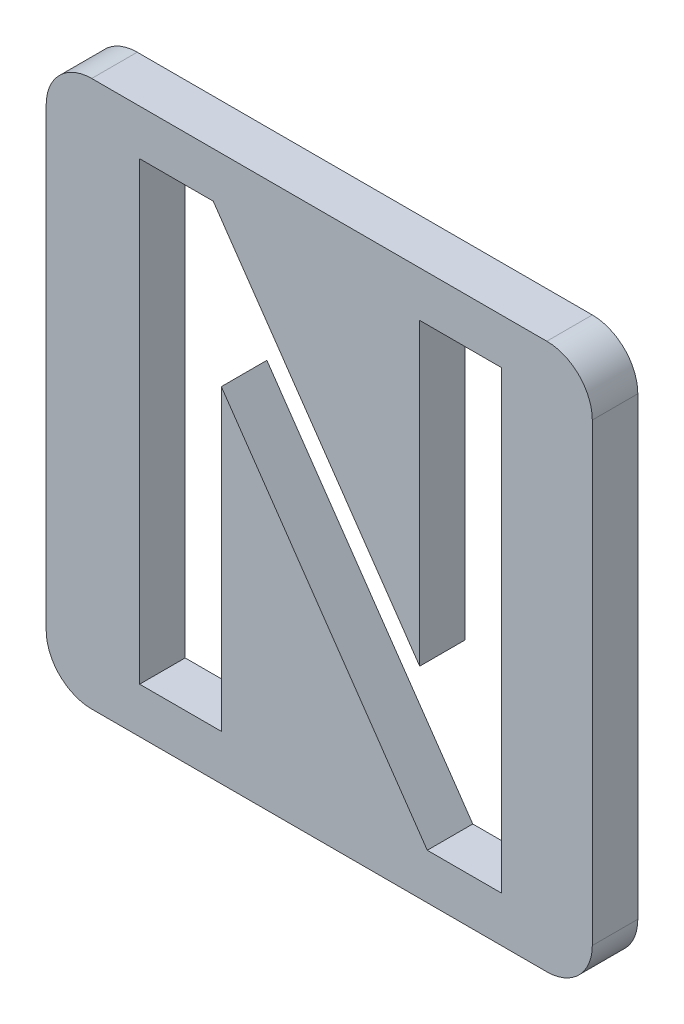
SolidWorks part; units mm, degrees
ref_plane "Front Plane" through (0, 0, 0) normal (0, 0, 1) x (1, 0, 0)
ref_plane "Top Plane" through (0, 0, 0) normal (0, 1, 0) x (1, 0, 0)
ref_plane "Right Plane" through (0, 0, 0) normal (1, 0, 0) x (0, 0, -1)
sketch "Sketch1" plane through (0, 0, 0) normal (0, 0, 1) x (1, 0, 0)
  line L1 (-50, 60) -> (50, 60)
  line L2 (-60, 50) -> (-60, -50)
  line L3 (-50, -60) -> (50, -60)
  line L4 (60, 50) -> (60, -50)
  line L5 (-60, 60) -> (60, -60) construction
  line L6 (-60, -60) -> (60, 60) construction
  arc A0 (-60, -50) -> (-50, -60) centre (-50, -50) ccw
  arc A1 (50, -60) -> (60, -50) centre (50, -50) ccw
  arc A2 (50, 60) -> (60, 50) centre (50, 50) cw
  arc A3 (-50, 60) -> (-60, 50) centre (-50, 50) ccw
  point P0 (0, 0)
  dimension "D3" = 10
  dimension "D1" = 120
  dimension "D2" = 120
extrude "Boss-Extrude1" add sketch "Sketch1" along normal blind 10 contours A3 L2 A0 L3 A1 L4 A2 L1
sketch "Sketch2" plane through (0, 0, 10) normal (0, 0, 1) x (1, 0, 0)
  line L0 (0, 0) -> (0, 40) construction
  line L1 (-50, 50) -> (50, 50) construction
  line L2 (-50, 50) -> (-50, -50) construction
  line L3 (-50, -50) -> (50, -50) construction
  line L4 (50, 50) -> (50, -50) construction
  line L5 (-50, 50) -> (50, -50) construction
  line L6 (-50, -50) -> (50, 50) construction
  line L7 (0, 40) -> (-40, 40) construction
  line L8 (-40, 40) -> (-40, 0) construction
  line L9 (-40, 0) -> (0, 0) construction
  line L11 (0, 20) -> (-20, 20) construction
  line L12 (-20, 40) -> (-20, 20) construction
  circle A0 centre (0, 40) radius 4 construction
  circle A1 centre (0, 20) radius 4 construction
  circle A2 centre (0, 0) radius 4 construction
  circle A3 centre (-20, 20) radius 4 construction
  circle A4 centre (-20, 40) radius 4 construction
  circle A5 centre (-40, 40) radius 4 construction
  circle A6 centre (0, 0) radius 4 construction
  circle A7 centre (20, 0) radius 4 construction
  circle A8 centre (40, 0) radius 4 construction
  circle A9 centre (40, 20) radius 4 construction
  circle A10 centre (40, 40) radius 4 construction
  circle A11 centre (20, 20) radius 4 construction
  circle A12 centre (0, 0) radius 4 construction
  circle A13 centre (0, -20) radius 4 construction
  circle A14 centre (0, -40) radius 4 construction
  circle A15 centre (20, -40) radius 4 construction
  circle A16 centre (40, -40) radius 4 construction
  circle A17 centre (20, -20) radius 4 construction
  circle A18 centre (0, 0) radius 4 construction
  circle A19 centre (-20, 0) radius 4 construction
  circle A20 centre (-40, 0) radius 4 construction
  circle A21 centre (-40, -20) radius 4 construction
  circle A22 centre (-40, -40) radius 4 construction
  circle A23 centre (-20, -20) radius 4 construction
  text T0 "N" font "Century Gothic" height 100
  point P0 (0, 0)
  point P55 (0, 0)
  dimension "D4" = 8
  dimension "D1" = 100
  dimension "D2" = 100
  dimension "D3" = 40
  dimension "D5" = 4
extrude "Cut-Extrude27" cut sketch "Sketch2" against normal blind 10
